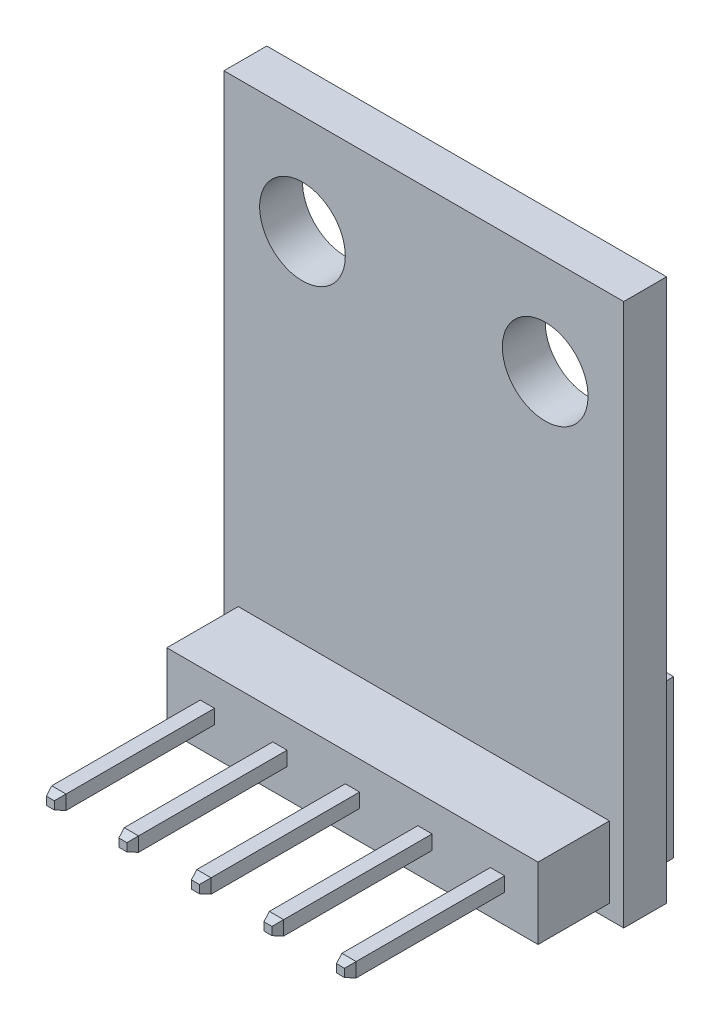
SolidWorks part; units mm, degrees
material "Hot Galvanized Steel"
ref_plane "Front" through (0, 0, 0) normal (0, 0, 1) x (1, 0, 0)
ref_plane "Top" through (0, 0, 0) normal (0, 1, 0) x (1, 0, 0)
ref_plane "Right" through (0, 0, 0) normal (1, 0, 0) x (0, 0, -1)
sketch "Sketch2" plane through (0, 0, 0) normal (0, 0, 1) x (1, 0, 0)
  line L1 (-7, 9.5) -> (7, 9.5)
  line L2 (-7, 9.5) -> (-7, -9.5)
  line L3 (-7, -9.5) -> (7, -9.5)
  line L4 (7, 9.5) -> (7, -9.5)
  line L5 (-7, 9.5) -> (7, -9.5) construction
  line L6 (-7, -9.5) -> (7, 9.5) construction
  point P0 (0, 0)
  dimension "D1" = 14
  dimension "D2" = 19
extrude "Boss-Extrude1" add sketch "Sketch2" along normal blind 1.5
sketch "Sketch3" plane through (0, 0, 1.5) normal (0, 0, 1) x (1, 0, 0)
  line L0 (0, 9.5) -> (0, 0) construction
  line L1 (7, 9.5) -> (-7, 9.5) construction
  circle A0 centre (-4.25, 6) radius 1.5
  circle A1 centre (4.25, 6) radius 1.5
  dimension "D1" = 8.5
  dimension "D2" = 3
  dimension "D3" = 3.5
extrude "Cut-Extrude1" cut sketch "Sketch3" against normal through all
sketch "Sketch4" plane through (0, 0, 1.5) normal (0, 0, 1) x (1, 0, 0)
  line L0 (-7, -9.5) -> (7, -9.5) construction
  line L1 (-6.5, -6.5) -> (6.5, -6.5)
  line L2 (-6.5, -6.5) -> (-6.5, -9)
  line L3 (-6.5, -9) -> (6.5, -9)
  line L4 (6.5, -6.5) -> (6.5, -9)
  line L5 (-6.5, -6.5) -> (6.5, -9) construction
  line L6 (-6.5, -9) -> (6.5, -6.5) construction
  point P0 (0, -7.75)
  point P5 (0, 0)
  dimension "D1" = 2.5
  dimension "D2" = 13
  dimension "D3" = 0.5
extrude "Boss-Extrude2" add sketch "Sketch4" along normal blind 2.5
sketch "Sketch5" plane through (0, 0, 4) normal (0, 0, 1) x (1, 0, 0)
  line L0 (-6.5, -6.5) -> (-6.5, -9) construction
  line L1 (-5.33, -7.5) -> (-4.83, -7.5)
  line L2 (-5.33, -7.5) -> (-5.33, -8)
  line L3 (-5.33, -8) -> (-4.83, -8)
  line L4 (-4.83, -7.5) -> (-4.83, -8)
  line L5 (-5.33, -7.5) -> (-4.83, -8) construction
  line L6 (-5.33, -8) -> (-4.83, -7.5) construction
  line L7 (-2.79, -7.5) -> (-2.29, -7.5)
  line L8 (-2.79, -7.5) -> (-2.79, -8)
  line L9 (-2.79, -8) -> (-2.29, -8)
  line L10 (-2.29, -7.5) -> (-2.29, -8)
  line L11 (-2.79, -7.5) -> (-2.29, -8) construction
  line L12 (-2.79, -8) -> (-2.29, -7.5) construction
  line L13 (-0.25, -7.5) -> (0.25, -7.5)
  line L14 (-0.25, -7.5) -> (-0.25, -8)
  line L15 (-0.25, -8) -> (0.25, -8)
  line L16 (0.25, -7.5) -> (0.25, -8)
  line L17 (-0.25, -7.5) -> (0.25, -8) construction
  line L18 (-0.25, -8) -> (0.25, -7.5) construction
  line L19 (2.29, -7.5) -> (2.79, -7.5)
  line L20 (2.29, -7.5) -> (2.29, -8)
  line L21 (2.29, -8) -> (2.79, -8)
  line L22 (2.79, -7.5) -> (2.79, -8)
  line L23 (2.29, -7.5) -> (2.79, -8) construction
  line L24 (2.29, -8) -> (2.79, -7.5) construction
  line L25 (4.83, -7.5) -> (5.33, -7.5)
  line L26 (4.83, -7.5) -> (4.83, -8)
  line L27 (4.83, -8) -> (5.33, -8)
  line L28 (5.33, -7.5) -> (5.33, -8)
  line L29 (4.83, -7.5) -> (5.33, -8) construction
  line L30 (4.83, -8) -> (5.33, -7.5) construction
  line L31 (-5.08, -7.75) -> (-2.54, -7.75) construction
  point P0 (-5.08, -7.75)
  point P7 (-6.5, -7.75)
  point P8 (0, 0)
  point P9 (-2.54, -7.75)
  point P14 (0, -7.75)
  point P19 (2.54, -7.75)
  point P24 (5.08, -7.75)
  dimension "D1" = 0.5
  dimension "D2" = 5
  dimension "D3" = 2.54
extrude "Boss-Extrude3" add sketch "Sketch5" along normal blind 5.5
chamfer "Chamfer1" distance 0.3 angle 20 20 edges at (5.08, -8, 9.5) (4.83, -7.75, 9.5) (5.08, -7.5, 9.5) (5.33, -7.75, 9.5) (2.54, -8, 9.5) (2.29, -7.75, 9.5) (2.54, -7.5, 9.5) (2.79, -7.75, 9.5) (0, -8, 9.5) (-0.25, -7.75, 9.5) (0, -7.5, 9.5) (0.25, -7.75, 9.5) (-2.54, -8, 9.5) (-2.79, -7.75, 9.5) (-2.54, -7.5, 9.5) (-2.29, -7.75, 9.5) (-5.08, -8, 9.5) (-5.33, -7.75, 9.5) (-5.08, -7.5, 9.5) (-4.83, -7.75, 9.5)
sketch "Sketch6" plane through (0, 0, 0) normal (0, 0, -1) x (-1, 0, 0)
  line L0 (7, -9.5) -> (-7, -9.5) construction
  line L1 (-6.25, -3.5) -> (6.25, -3.5)
  line L2 (-6.25, -3.5) -> (-6.25, -9)
  line L3 (-6.25, -9) -> (6.25, -9)
  line L4 (6.25, -3.5) -> (6.25, -9)
  line L5 (-6.25, -3.5) -> (6.25, -9) construction
  line L6 (-6.25, -9) -> (6.25, -3.5) construction
  line L7 (-2.25, 2.5) -> (2.25, 2.5)
  line L8 (-2.25, 2.5) -> (-2.25, 1)
  line L9 (-2.25, 1) -> (2.25, 1)
  line L10 (2.25, 2.5) -> (2.25, 1)
  line L11 (-2.25, 2.5) -> (2.25, 1) construction
  line L12 (-2.25, 1) -> (2.25, 2.5) construction
  line L13 (-1.25, 6.5) -> (1.25, 6.5)
  line L14 (-1.25, 6.5) -> (-1.25, 5.5)
  line L15 (-1.25, 5.5) -> (1.25, 5.5)
  line L16 (1.25, 6.5) -> (1.25, 5.5)
  line L17 (-1.25, 6.5) -> (1.25, 5.5) construction
  line L18 (-1.25, 5.5) -> (1.25, 6.5) construction
  line L19 (-1.25, 5) -> (1.25, 5)
  line L20 (-1.25, 5) -> (-1.25, 4)
  line L21 (-1.25, 4) -> (1.25, 4)
  line L22 (1.25, 5) -> (1.25, 4)
  line L23 (-1.25, 5) -> (1.25, 4) construction
  line L24 (-1.25, 4) -> (1.25, 5) construction
  line L25 (-7, 9.5) -> (7, 9.5) construction
  point P0 (0, -6.25)
  point P5 (0, 1.75)
  point P10 (0, 6)
  point P15 (0, 4.5)
  point P20 (0, 0)
  point P21 (0, 0)
  point P23 (0, 0)
  point P24 (0, 0)
  point P29 (0, 4.0067)
  dimension "D1" = 12.5
  dimension "D2" = 5.5
  dimension "D3" = 0.5
  dimension "D4" = 4.5
  dimension "D5" = 1.5
  dimension "D6" = 7
  dimension "D7" = 1
  dimension "D8" = 0.5
  dimension "D9" = 2.5
  dimension "D10" = 3
extrude "Koponenttien tilavaraus" add sketch "Sketch6" along normal blind 1
